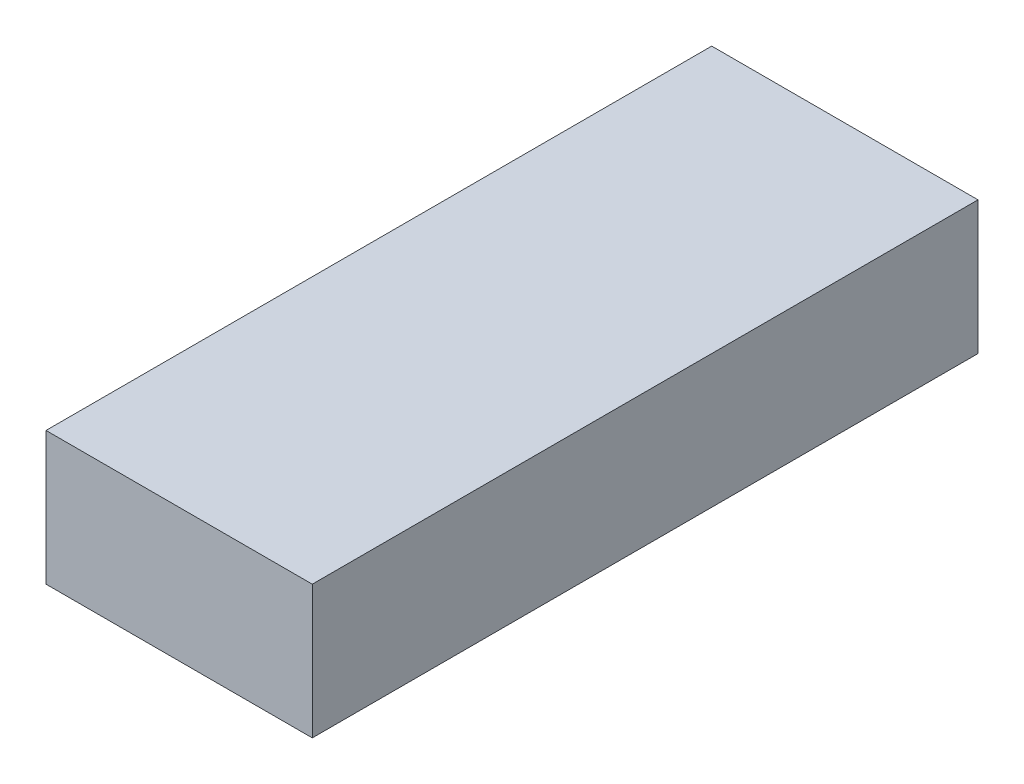
SolidWorks part; units mm, degrees
material "POLYURETHANE (11671)"
ref_plane "Front Plane" through (0, 0, 0) normal (0, 0, 1) x (1, 0, 0)
ref_plane "Top Plane" through (0, 0, 0) normal (0, 1, 0) x (1, 0, 0)
ref_plane "Right Plane" through (0, 0, 0) normal (1, 0, 0) x (0, 0, -1)
sketch "Sketch1" plane through (0, 0, 0) normal (0, 1, 0) x (1, 0, 0)
  line L1 (0, 0) -> (6.35, 0)
  line L2 (0, 0) -> (0, 15.875)
  line L3 (0, 15.875) -> (6.35, 15.875)
  line L4 (6.35, 0) -> (6.35, 15.875)
  dimension "D1" = 6.35
  dimension "D2" = 15.875
extrude "Boss-Extrude1" add sketch "Sketch1" along normal blind 3.175
